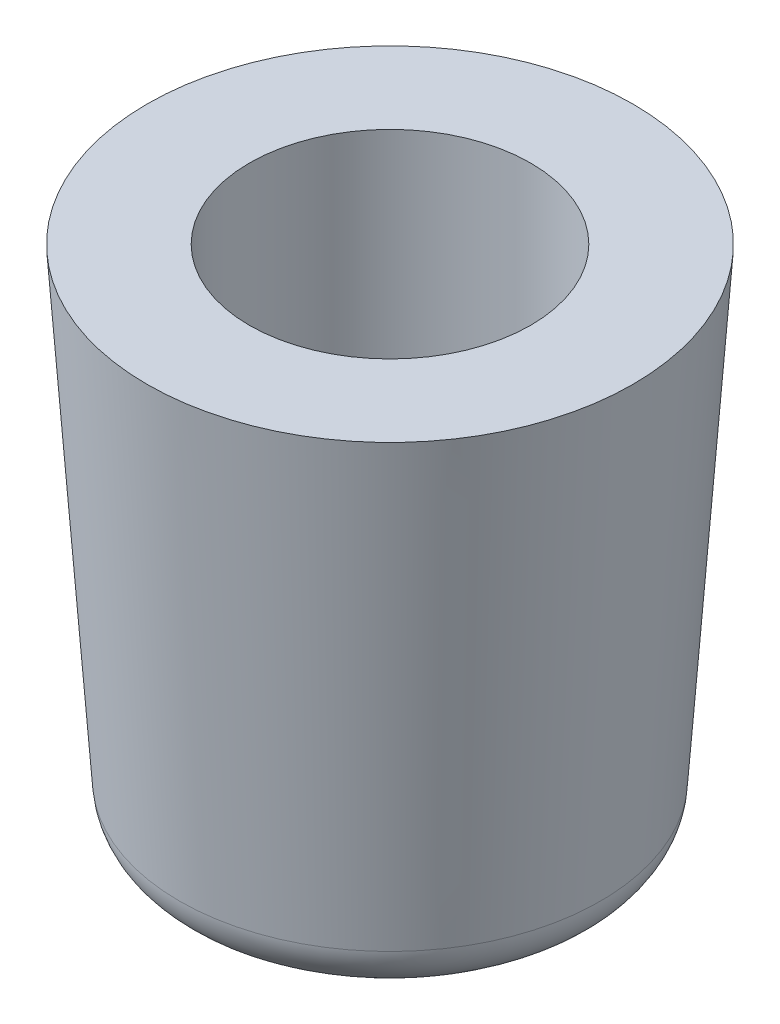
SolidWorks part; units mm, degrees
material "BUTYL"
ref_plane "Front Plane" through (0, 0, 0) normal (0, 0, 1) x (1, 0, 0)
ref_plane "Top Plane" through (0, 0, 0) normal (0, 1, 0) x (1, 0, 0)
ref_plane "Right Plane" through (0, 0, 0) normal (1, 0, 0) x (0, 0, -1)
sketch "Sketch1" plane through (0, 0, 0) normal (0, 1, 0) x (1, 0, 0)
  circle A0 centre (0, 0) radius 4.75
  dimension "D1" = 9.5
extrude "Boss-Extrude1" add sketch "Sketch1" against normal blind 10 draft 4
sketch "Sketch2" plane through (0, 0, 0) normal (0, 1, 0) x (1, 0, 0)
  circle A0 centre (0, 0) radius 2.75
  dimension "D1" = 5.5
extrude "Cut-Extrude1" cut sketch "Sketch2" against normal blind 4
fillet "Fillet1" radius 1 1 edges at (0, -10, 4.0507)
